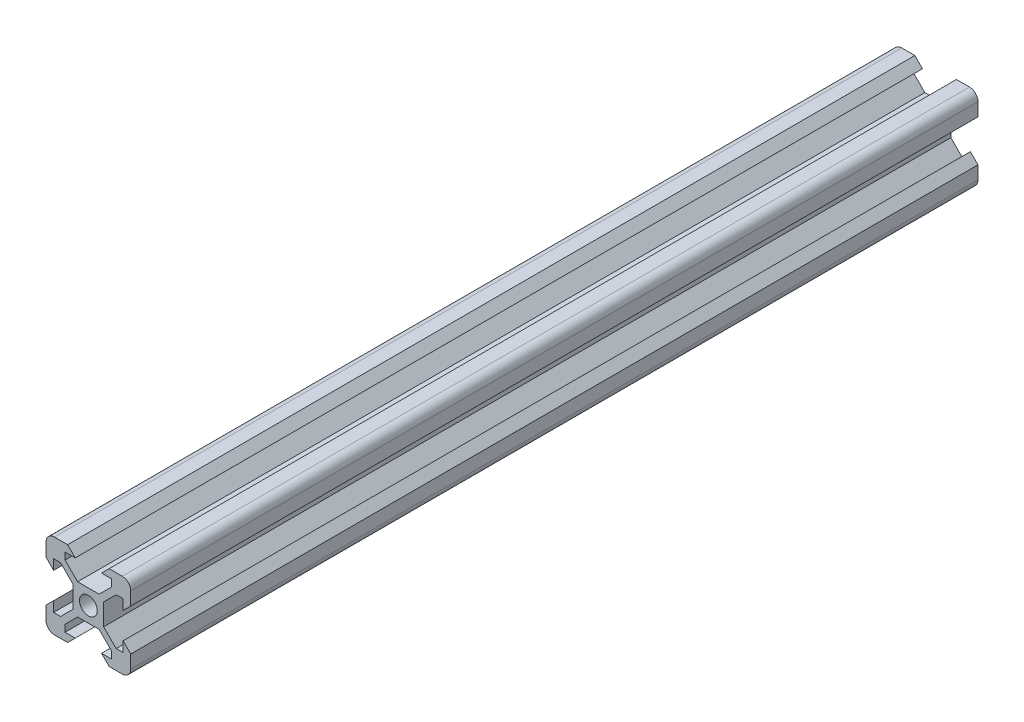
SolidWorks part; units mm, degrees
material "6061 Alloy"
ref_plane "Front Plane" through (0, 0, 0) normal (0, 0, 1) x (1, 0, 0)
ref_plane "Top Plane" through (0, 0, 0) normal (0, 1, 0) x (1, 0, 0)
ref_plane "Right Plane" through (0, 0, 0) normal (1, 0, 0) x (0, 0, -1)
sketch "Sketch1" plane through (0, 0, 0) normal (0, 0, 1) x (1, 0, 0)
  line L0 (-4.9, -10) -> (-5.5, -10)
  line L1 (-10, -10) -> (10, -10) construction
  line L2 (-10, -10) -> (-10, 10) construction
  line L3 (-10, 10) -> (10, 10) construction
  line L4 (10, -10) -> (10, 10) construction
  line L5 (-10, -10) -> (10, 10) construction
  line L6 (-10, 10) -> (10, -10) construction
  line L7 (-3.6, 3.6) -> (3.6, 3.6)
  line L8 (-3.6, 3.6) -> (-3.6, -3.6)
  line L9 (-3.6, -3.6) -> (3.6, -3.6)
  line L10 (3.6, 3.6) -> (3.6, -3.6)
  line L11 (-8, 10) -> (-5.5, 10)
  line L12 (-10, 8) -> (-10, 5.5)
  line L13 (-10, 5.5) -> (-5.5, 5.5)
  line L14 (-5.5, 10) -> (-5.5, 5.5)
  line L15 (8, 10) -> (5.5, 10)
  line L16 (10, 8) -> (10, 5.5)
  line L17 (10, 5.5) -> (5.5, 5.5)
  line L18 (5.5, 10) -> (5.5, 5.5)
  line L19 (8, -10) -> (5.5, -10)
  line L20 (10, -8) -> (10, -5.5)
  line L21 (10, -5.5) -> (5.5, -5.5)
  line L22 (5.5, -10) -> (5.5, -5.5)
  line L23 (-8, -10) -> (-5.5, -10)
  line L24 (-10, -8) -> (-10, -5.5)
  line L25 (-10, -5.5) -> (-5.5, -5.5)
  line L26 (-5.5, -10) -> (-5.5, -5.5)
  line L27 (-3.1, -8.2) -> (-4.9, -10)
  line L28 (-3.1, -8.2) -> (-5.5, -8.2)
  line L29 (4.9, -10) -> (5.5, -10)
  line L30 (3.1, -8.2) -> (4.9, -10)
  line L31 (3.1, -8.2) -> (5.5, -8.2)
  line L32 (-4.9, 10) -> (-5.5, 10)
  line L33 (-3.1, 8.2) -> (-4.9, 10)
  line L34 (-3.1, 8.2) -> (-5.5, 8.2)
  line L35 (4.9, 10) -> (5.5, 10)
  line L36 (0, 0) -> (17.4618, 0) construction
  line L37 (3.1, 8.2) -> (4.9, 10)
  line L38 (3.1, 8.2) -> (5.5, 8.2)
  line L39 (8.2, 3.1) -> (8.2, 5.5)
  line L40 (8.2, 3.1) -> (10, 4.9)
  line L41 (10, 4.9) -> (10, 5.5)
  line L42 (10, -4.9) -> (10, -5.5)
  line L43 (8.2, -3.1) -> (10, -4.9)
  line L44 (8.2, -3.1) -> (8.2, -5.5)
  line L57 (-8.2, -3.1) -> (-10, -4.9)
  line L58 (-10, -4.9) -> (-10, -5.5)
  line L61 (-8.2, -3.1) -> (-8.2, -5.5)
  line L62 (-8.2, 3.1) -> (-10, 4.9)
  line L63 (-10, 4.9) -> (-10, 5.5)
  line L66 (-8.2, 3.1) -> (-8.2, 5.5)
  line L67 (-2.7729, 2.7729) -> (-6.4508, 6.4508) construction
  line L68 (-2.2426, 3.3033) -> (-5.9205, 6.9812)
  line L69 (-3.3033, 2.2426) -> (-6.9812, 5.9205)
  line L70 (6.7372, 6.7372) -> (2.7729, 2.7729)
  line L71 (6.309, -6.309) -> (2.7729, -2.7729)
  line L72 (-2.8687, -2.8687) -> (-6.5971, -6.5971)
  line L73 (6.2069, 7.2675) -> (2.2426, 3.3033)
  line L74 (6.8393, -5.7786) -> (3.3033, -2.2426)
  line L75 (-3.399, -2.3384) -> (-7.1274, -6.0667)
  line L76 (7.2675, 6.2069) -> (3.3033, 2.2426)
  line L77 (5.7786, -6.8393) -> (2.2426, -3.3033)
  line L78 (-2.3384, -3.399) -> (-6.0667, -7.1274)
  circle A0 centre (0, 0) radius 2.1
  arc A1 (-8, -10) -> (-10, -8) centre (-8, -8) cw
  arc A2 (8, -10) -> (10, -8) centre (8, -8) ccw
  arc A3 (8, 10) -> (10, 8) centre (8, 8) cw
  arc A4 (-8, 10) -> (-10, 8) centre (-8, 8) ccw
  point P0 (0, 0)
  dimension "D3" = 4.2
  dimension "D12" = 2
  dimension "D1" = 20
  dimension "D4" = 6.4
  dimension "D5" = 6.4
  dimension "D6" = 6.4
  dimension "D7" = 6.4
  dimension "D8" = 4.5
  dimension "D9" = 4.5
  dimension "D10" = 4.5
  dimension "D11" = 4.5
  dimension "D13" = 45
  dimension "D19" = 45
  dimension "D20" = 6.2
  dimension "D23" = 1.8
  dimension "D24" = 1.8
  dimension "D28" = 0.75
  dimension "D26" = 0.75
  dimension "D27" = 0.75
  dimension "D29" = 0.75
extrude "Boss-Extrude1" add sketch "Sketch1" along normal blind 200
